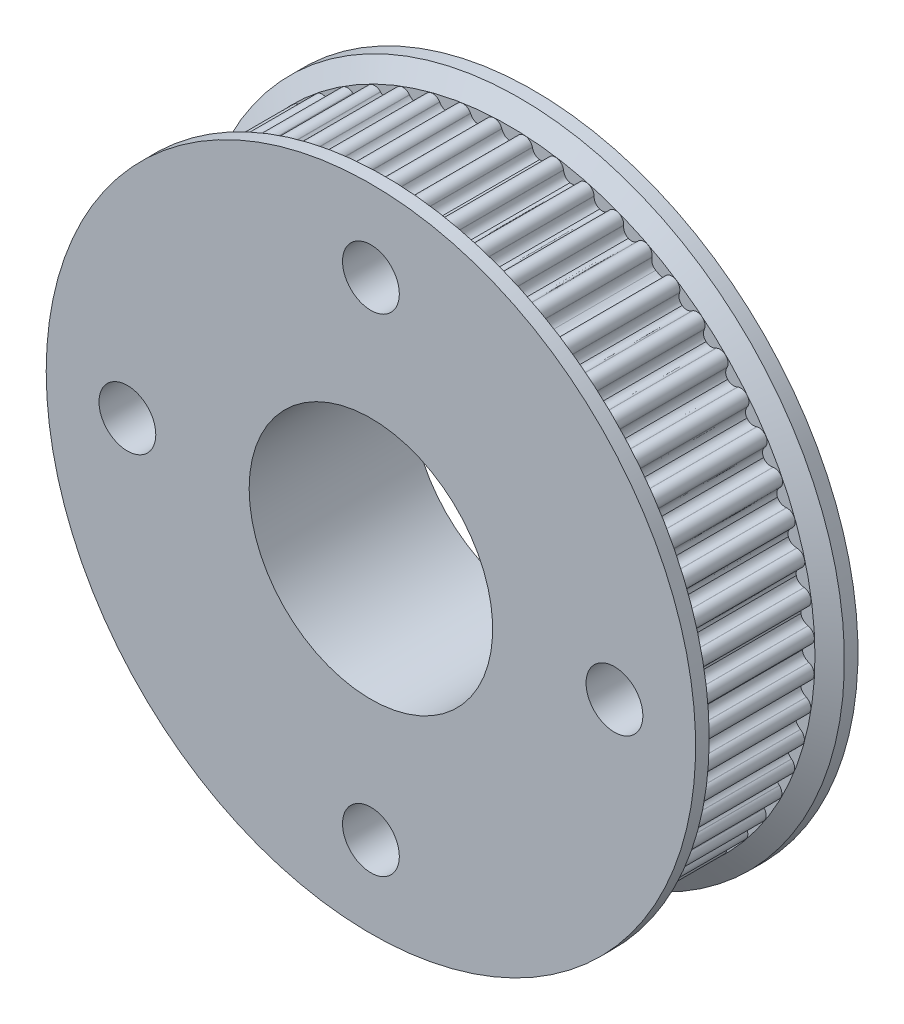
SolidWorks part; units mm, degrees
other "Camera1"
other "Camera2"
other "Camera3"
ref_plane "Front" through (0, 0, 0) normal (0, 0, 1) x (1, 0, 0)
ref_plane "Top" through (0, 0, 0) normal (0, 1, 0) x (1, 0, 0)
ref_plane "Right" through (0, 0, 0) normal (1, 0, 0) x (0, 0, -1)
sketch "Sketch1" plane through (0, 0, 0) normal (1, 0, 0) x (0, 0, -1)
  line L0 (0, 0) -> (-24.4032, 0) construction
  line L3 (0, 7.5) -> (0, 18.3141)
  line L4 (-1.5, 18.85) -> (-8.5, 18.85)
  line L5 (-10, 20) -> (-10, 7.5)
  line L6 (-10, 7.5) -> (0, 7.5)
  line L7 (0, 18.3141) -> (0, 20)
  line L9 (-0.836, 20) -> (-1.5, 18.85)
  line L10 (-10, 13.3586) -> (0, 13.3586) construction
  line L11 (-5, 18.85) -> (-5, 22.0506) construction
  line L12 (-9.164, 20) -> (-8.5, 18.85)
  line L15 (-10, 20) -> (-8.5, 18.85) construction
  line L16 (-1.5, 18.85) -> (0, 18.3141) construction
  line L17 (-10, 20) -> (-9.164, 20)
  line L18 (-0.836, 20) -> (0, 20)
  point P24 (-5, 13.3586)
  dimension "D2" = 10
  dimension "D3" = 7
  dimension "D4" = 37.7
  dimension "D5" = 40
  dimension "D6" = 120
  dimension "D8" = 15
revolve "Revolve1" add sketch "Sketch1" angle 360 about L0
ref_plane "Plane2" through (0, 0, 1.5) normal (0, 0, 1) x (1, 0, 0)
ref_plane "Plane3" through (0, 0, 8.5) normal (0, 0, 1) x (1, 0, 0)
sketch "Sketch3" plane through (0, 0, 1.5) normal (0, 0, 1) x (1, 0, 0)
  line L0 (0.4895, 18.4804) -> (0.4858, 18.4697)
  line L1 (-0.4323, 18.471) -> (-0.436, 18.4817)
  line L2 (-1.3914, 18.4344) -> (-1.394, 18.4234)
  line L3 (-2.3607, 18.3247) -> (-2.3654, 18.3349)
  line L4 (-3.3107, 18.188) -> (-3.3122, 18.1768)
  line L5 (-4.2632, 17.9775) -> (-4.269, 17.9872)
  line L6 (-5.1937, 17.7423) -> (-5.194, 17.731)
  line L7 (-6.119, 17.4334) -> (-6.1258, 17.4424)
  line L8 (-7.0199, 17.1022) -> (-7.019, 17.0909)
  line L9 (-7.9078, 16.6983) -> (-7.9155, 16.7066)
  line L10 (-8.7691, 16.2747) -> (-8.767, 16.2636)
  line L11 (-9.6099, 15.7803) -> (-9.6184, 15.7877)
  line L12 (-10.4222, 15.269) -> (-10.419, 15.2581)
  line L13 (-11.2067, 14.6893) -> (-11.216, 14.6958)
  line L14 (-11.9612, 14.0959) -> (-11.9568, 14.0855)
  line L15 (-12.6808, 13.4374) -> (-12.6907, 13.4429)
  line L16 (-13.3691, 12.7684) -> (-13.3637, 12.7585)
  line L17 (-14.0159, 12.0383) -> (-14.0263, 12.0427)
  line L18 (-14.6305, 11.301) -> (-14.6241, 11.2917)
  line L19 (-15.1975, 10.5073) -> (-15.2083, 10.5106)
  line L20 (-15.7316, 9.7098) -> (-15.7243, 9.7012)
  line L21 (-16.2125, 8.8612) -> (-16.2236, 8.8633)
  line L22 (-16.6604, 8.0122) -> (-16.6522, 8.0044)
  line L23 (-17.05, 7.118) -> (-17.0612, 7.1189)
  line L24 (-17.4066, 6.2268) -> (-17.3977, 6.22)
  line L25 (-17.7006, 5.2968) -> (-17.7119, 5.2965)
  line L26 (-17.9621, 4.3732) -> (-17.9525, 4.3673)
  line L27 (-18.1573, 3.4175) -> (-18.1685, 3.4161)
  line L28 (-18.3209, 2.4717) -> (-18.3107, 2.4669)
  line L29 (-18.415, 1.5008) -> (-18.426, 1.4983)
  line L30 (-18.4789, 0.5431) -> (-18.4682, 0.5394)
  line L31 (-18.471, -0.4323) -> (-18.4817, -0.436)
  line L32 (-18.4344, -1.3914) -> (-18.4234, -1.394)
  line L33 (-18.3247, -2.3607) -> (-18.3349, -2.3654)
  line L34 (-18.188, -3.3107) -> (-18.1768, -3.3122)
  line L35 (-17.9775, -4.2632) -> (-17.9872, -4.269)
  line L36 (-17.7423, -5.1937) -> (-17.731, -5.194)
  line L37 (-17.4334, -6.119) -> (-17.4424, -6.1258)
  line L38 (-17.1022, -7.0199) -> (-17.0909, -7.019)
  line L39 (-16.6983, -7.9078) -> (-16.7066, -7.9155)
  line L40 (-16.2747, -8.7691) -> (-16.2636, -8.767)
  line L41 (-15.7803, -9.6099) -> (-15.7877, -9.6184)
  line L42 (-15.269, -10.4222) -> (-15.2581, -10.419)
  line L43 (-14.6893, -11.2067) -> (-14.6958, -11.216)
  line L44 (-14.0959, -11.9612) -> (-14.0855, -11.9568)
  line L45 (-13.4374, -12.6808) -> (-13.4429, -12.6907)
  line L46 (-12.7684, -13.3691) -> (-12.7585, -13.3637)
  line L47 (-12.0383, -14.0159) -> (-12.0427, -14.0263)
  line L48 (-11.301, -14.6305) -> (-11.2917, -14.6241)
  line L49 (-10.5073, -15.1975) -> (-10.5106, -15.2083)
  line L50 (-9.7098, -15.7316) -> (-9.7012, -15.7243)
  line L51 (-8.8612, -16.2125) -> (-8.8633, -16.2236)
  line L52 (-8.0122, -16.6604) -> (-8.0044, -16.6522)
  line L53 (-7.118, -17.05) -> (-7.1189, -17.0612)
  line L54 (-6.2268, -17.4066) -> (-6.22, -17.3977)
  line L55 (-5.2968, -17.7006) -> (-5.2965, -17.7119)
  line L56 (-4.3732, -17.9621) -> (-4.3673, -17.9525)
  line L57 (-3.4175, -18.1573) -> (-3.4161, -18.1685)
  line L58 (-2.4717, -18.3209) -> (-2.4669, -18.3107)
  line L59 (-1.5008, -18.415) -> (-1.4983, -18.426)
  line L60 (-0.5431, -18.4789) -> (-0.5394, -18.4682)
  line L61 (0.4323, -18.471) -> (0.436, -18.4817)
  line L62 (1.3914, -18.4344) -> (1.394, -18.4234)
  line L63 (2.3607, -18.3247) -> (2.3654, -18.3349)
  line L64 (3.3107, -18.188) -> (3.3122, -18.1768)
  line L65 (4.2632, -17.9775) -> (4.269, -17.9872)
  line L66 (5.1937, -17.7423) -> (5.194, -17.731)
  line L67 (6.119, -17.4334) -> (6.1258, -17.4424)
  line L68 (7.0199, -17.1022) -> (7.019, -17.0909)
  line L69 (7.9078, -16.6983) -> (7.9155, -16.7066)
  line L70 (8.7691, -16.2747) -> (8.767, -16.2636)
  line L71 (9.6099, -15.7803) -> (9.6184, -15.7877)
  line L72 (10.4222, -15.269) -> (10.419, -15.2581)
  line L73 (11.2067, -14.6893) -> (11.216, -14.6958)
  line L74 (11.9612, -14.0959) -> (11.9568, -14.0855)
  line L75 (12.6808, -13.4374) -> (12.6907, -13.4429)
  line L76 (13.3691, -12.7684) -> (13.3637, -12.7585)
  line L77 (14.0159, -12.0383) -> (14.0263, -12.0427)
  line L78 (14.6305, -11.301) -> (14.6241, -11.2917)
  line L79 (15.1975, -10.5073) -> (15.2083, -10.5106)
  line L80 (15.7316, -9.7098) -> (15.7243, -9.7012)
  line L81 (16.2125, -8.8612) -> (16.2236, -8.8633)
  line L82 (16.6604, -8.0122) -> (16.6522, -8.0044)
  line L83 (17.05, -7.118) -> (17.0612, -7.1189)
  line L84 (17.4066, -6.2268) -> (17.3977, -6.22)
  line L85 (17.7006, -5.2968) -> (17.7119, -5.2965)
  line L86 (17.9621, -4.3732) -> (17.9525, -4.3673)
  line L87 (18.1573, -3.4175) -> (18.1685, -3.4161)
  line L88 (18.3209, -2.4717) -> (18.3107, -2.4669)
  line L89 (18.415, -1.5008) -> (18.426, -1.4983)
  line L90 (18.4789, -0.5431) -> (18.4682, -0.5394)
  line L91 (18.471, 0.4323) -> (18.4817, 0.436)
  line L92 (18.4344, 1.3914) -> (18.4234, 1.394)
  line L93 (18.3247, 2.3607) -> (18.3349, 2.3654)
  line L94 (18.188, 3.3107) -> (18.1768, 3.3122)
  line L95 (17.9775, 4.2632) -> (17.9872, 4.269)
  line L96 (17.7423, 5.1937) -> (17.731, 5.194)
  line L97 (17.4334, 6.119) -> (17.4424, 6.1258)
  line L98 (17.1022, 7.0199) -> (17.0909, 7.019)
  line L99 (16.6983, 7.9078) -> (16.7066, 7.9155)
  line L100 (16.2747, 8.7691) -> (16.2636, 8.767)
  line L101 (15.7803, 9.6099) -> (15.7877, 9.6184)
  line L102 (15.269, 10.4222) -> (15.2581, 10.419)
  line L103 (14.6893, 11.2067) -> (14.6958, 11.216)
  line L104 (14.0959, 11.9612) -> (14.0855, 11.9568)
  line L105 (13.4374, 12.6808) -> (13.4429, 12.6907)
  line L106 (12.7684, 13.3691) -> (12.7585, 13.3637)
  line L107 (12.0383, 14.0159) -> (12.0427, 14.0263)
  line L108 (11.301, 14.6305) -> (11.2917, 14.6241)
  line L109 (10.5073, 15.1975) -> (10.5106, 15.2083)
  line L110 (9.7098, 15.7316) -> (9.7012, 15.7243)
  line L111 (8.8141, 16.2382) -> (8.8162, 16.2492)
  line L112 (7.9639, 16.6835) -> (7.9561, 16.6753)
  line L113 (7.0685, 17.0705) -> (7.0694, 17.0818)
  line L114 (6.1763, 17.4246) -> (6.1695, 17.4156)
  line L115 (5.2454, 17.7159) -> (5.2452, 17.7272)
  line L116 (4.3211, 17.9748) -> (4.3153, 17.9651)
  line L117 (3.3649, 18.1671) -> (3.3634, 18.1783)
  line L118 (2.4186, 18.328) -> (2.4138, 18.3178)
  line L119 (1.4475, 18.4193) -> (1.4449, 18.4303)
  arc A0 (-0.436, 18.4817) -> (-1.3914, 18.4344) centre (-0.9065, 18.3126) ccw
  arc A1 (-2.3654, 18.3349) -> (-3.3107, 18.188) centre (-2.8157, 18.1175) ccw
  arc A2 (-4.269, 17.9872) -> (-5.1937, 17.7423) centre (-4.6941, 17.7239) ccw
  arc A3 (-6.1258, 17.4424) -> (-7.0199, 17.1022) centre (-6.521, 17.1362) ccw
  arc A4 (-7.9155, 16.7066) -> (-8.7691, 16.2747) centre (-8.2765, 16.3607) ccw
  arc A5 (-9.6184, 15.7877) -> (-10.4222, 15.269) centre (-9.9413, 15.4059) ccw
  arc A6 (-11.216, 14.6958) -> (-11.9612, 14.0959) centre (-11.4972, 14.2824) ccw
  arc A7 (-12.6907, 13.4429) -> (-13.3691, 12.7684) centre (-12.9272, 13.0023) ccw
  arc A8 (-14.0263, 12.0427) -> (-14.6305, 11.301) centre (-14.2155, 11.5798) ccw
  arc A9 (-15.2083, 10.5106) -> (-15.7316, 9.7098) centre (-15.348, 10.0305) ccw
  arc A10 (-16.2236, 8.8633) -> (-16.6604, 8.0122) centre (-16.3124, 8.3712) ccw
  arc A11 (-17.0612, 7.1189) -> (-17.4066, 6.2268) centre (-17.0981, 6.6203) ccw
  arc A12 (-17.7119, 5.2965) -> (-17.9621, 4.3732) centre (-17.6964, 4.7968) ccw
  arc A13 (-18.1685, 3.4161) -> (-18.3209, 2.4717) centre (-18.1009, 2.9207) ccw
  arc A14 (-18.426, 1.4983) -> (-18.4789, 0.5431) centre (-18.307, 1.0127) ccw
  arc A15 (-18.4817, -0.436) -> (-18.4344, -1.3914) centre (-18.3126, -0.9065) ccw
  arc A16 (-18.3349, -2.3654) -> (-18.188, -3.3107) centre (-18.1175, -2.8157) ccw
  arc A17 (-17.9872, -4.269) -> (-17.7423, -5.1937) centre (-17.7239, -4.6941) ccw
  arc A18 (-17.4424, -6.1258) -> (-17.1022, -7.0199) centre (-17.1362, -6.521) ccw
  arc A19 (-16.7066, -7.9155) -> (-16.2747, -8.7691) centre (-16.3607, -8.2765) ccw
  arc A20 (-15.7877, -9.6184) -> (-15.269, -10.4222) centre (-15.4059, -9.9413) ccw
  arc A21 (-14.6958, -11.216) -> (-14.0959, -11.9612) centre (-14.2824, -11.4972) ccw
  arc A22 (-13.4429, -12.6907) -> (-12.7684, -13.3691) centre (-13.0023, -12.9272) ccw
  arc A23 (-12.0427, -14.0263) -> (-11.301, -14.6305) centre (-11.5798, -14.2155) ccw
  arc A24 (-10.5106, -15.2083) -> (-9.7098, -15.7316) centre (-10.0305, -15.348) ccw
  arc A25 (-8.8633, -16.2236) -> (-8.0122, -16.6604) centre (-8.3712, -16.3124) ccw
  arc A26 (-7.1189, -17.0612) -> (-6.2268, -17.4066) centre (-6.6203, -17.0981) ccw
  arc A27 (-5.2965, -17.7119) -> (-4.3732, -17.9621) centre (-4.7968, -17.6964) ccw
  arc A28 (-3.4161, -18.1685) -> (-2.4717, -18.3209) centre (-2.9207, -18.1009) ccw
  arc A29 (-1.4983, -18.426) -> (-0.5431, -18.4789) centre (-1.0127, -18.307) ccw
  arc A30 (0.436, -18.4817) -> (1.3914, -18.4344) centre (0.9065, -18.3126) ccw
  arc A31 (2.3654, -18.3349) -> (3.3107, -18.188) centre (2.8157, -18.1175) ccw
  arc A32 (4.269, -17.9872) -> (5.1937, -17.7423) centre (4.6941, -17.7239) ccw
  arc A33 (6.1258, -17.4424) -> (7.0199, -17.1022) centre (6.521, -17.1362) ccw
  arc A34 (7.9155, -16.7066) -> (8.7691, -16.2747) centre (8.2765, -16.3607) ccw
  arc A35 (9.6184, -15.7877) -> (10.4222, -15.269) centre (9.9413, -15.4059) ccw
  arc A36 (11.216, -14.6958) -> (11.9612, -14.0959) centre (11.4972, -14.2824) ccw
  arc A37 (12.6907, -13.4429) -> (13.3691, -12.7684) centre (12.9272, -13.0023) ccw
  arc A38 (14.0263, -12.0427) -> (14.6305, -11.301) centre (14.2155, -11.5798) ccw
  arc A39 (15.2083, -10.5106) -> (15.7316, -9.7098) centre (15.348, -10.0305) ccw
  arc A40 (16.2236, -8.8633) -> (16.6604, -8.0122) centre (16.3124, -8.3712) ccw
  arc A41 (17.0612, -7.1189) -> (17.4066, -6.2268) centre (17.0981, -6.6203) ccw
  arc A42 (17.7119, -5.2965) -> (17.9621, -4.3732) centre (17.6964, -4.7968) ccw
  arc A43 (18.1685, -3.4161) -> (18.3209, -2.4717) centre (18.1009, -2.9207) ccw
  arc A44 (18.426, -1.4983) -> (18.4789, -0.5431) centre (18.307, -1.0127) ccw
  arc A45 (18.4817, 0.436) -> (18.4344, 1.3914) centre (18.3126, 0.9065) ccw
  arc A46 (18.3349, 2.3654) -> (18.188, 3.3107) centre (18.1175, 2.8157) ccw
  arc A47 (17.9872, 4.269) -> (17.7423, 5.1937) centre (17.7239, 4.6941) ccw
  arc A48 (17.4424, 6.1258) -> (17.1022, 7.0199) centre (17.1362, 6.521) ccw
  arc A49 (16.7066, 7.9155) -> (16.2747, 8.7691) centre (16.3607, 8.2765) ccw
  arc A50 (15.7877, 9.6184) -> (15.269, 10.4222) centre (15.4059, 9.9413) ccw
  arc A51 (14.6958, 11.216) -> (14.0959, 11.9612) centre (14.2824, 11.4972) ccw
  arc A52 (13.4429, 12.6907) -> (12.7684, 13.3691) centre (13.0023, 12.9272) ccw
  arc A53 (12.0427, 14.0263) -> (11.301, 14.6305) centre (11.5798, 14.2155) ccw
  arc A54 (10.5106, 15.2083) -> (9.7098, 15.7316) centre (10.0305, 15.348) ccw
  arc A55 (8.8162, 16.2492) -> (7.9639, 16.6835) centre (8.3239, 16.3366) ccw
  arc A56 (7.0694, 17.0818) -> (6.1763, 17.4246) centre (6.5707, 17.1172) ccw
  arc A57 (5.2452, 17.7272) -> (4.3211, 17.9748) centre (4.7454, 17.7103) ccw
  arc A58 (3.3634, 18.1783) -> (2.4186, 18.328) centre (2.8682, 18.1093) ccw
  arc A59 (1.4449, 18.4303) -> (0.4895, 18.4804) centre (0.9596, 18.3099) ccw
  spline S0 degree 3 poles (0.4858, 18.4697) (0.4077, 18.2495) (0.2403, 18.0862) (0.0262, 18.0851) knots 0 0 0 0 1 1 1 1
  spline S1 degree 3 poles (0.0262, 18.0851) (-0.1878, 18.0868) (-0.3548, 18.2506) (-0.4323, 18.471) knots 0 0 0 0 1 1 1 1
  spline S2 degree 3 poles (-1.394, 18.4234) (-1.4515, 18.1875) (-1.5982, 18.0156) (-1.8382, 17.9913) knots 0 0 0 0 1 1 1 1
  spline S3 degree 3 poles (-1.8382, 17.9913) (-2.0782, 17.9665) (-2.2567, 18.1053) (-2.3607, 18.3247) knots 0 0 0 0 1 1 1 1
  spline S4 degree 3 poles (-3.3122, 18.1768) (-3.3447, 17.9362) (-3.4726, 17.7498) (-3.7088, 17.7006) knots 0 0 0 0 1 1 1 1
  spline S5 degree 3 poles (-3.7088, 17.7006) (-3.9448, 17.6509) (-4.1368, 17.7702) (-4.2632, 17.9775) knots 0 0 0 0 1 1 1 1
  spline S6 degree 3 poles (-5.194, 17.731) (-5.2012, 17.4883) (-5.309, 17.2896) (-5.5387, 17.216) knots 0 0 0 0 1 1 1 1
  spline S7 degree 3 poles (-5.5387, 17.216) (-5.7682, 17.1418) (-5.9717, 17.2404) (-6.119, 17.4334) knots 0 0 0 0 1 1 1 1
  spline S8 degree 3 poles (-7.019, 17.0909) (-7.0007, 16.8488) (-7.0871, 16.6399) (-7.3079, 16.5427) knots 0 0 0 0 1 1 1 1
  spline S9 degree 3 poles (-7.3079, 16.5427) (-7.5284, 16.445) (-7.7411, 16.5218) (-7.9078, 16.6983) knots 0 0 0 0 1 1 1 1
  spline S10 degree 3 poles (-8.767, 16.2636) (-8.7236, 16.0248) (-8.7877, 15.808) (-8.9971, 15.6882) knots 0 0 0 0 1 1 1 1
  spline S11 degree 3 poles (-8.9971, 15.6882) (-9.2062, 15.568) (-9.4256, 15.6221) (-9.6099, 15.7803) knots 0 0 0 0 1 1 1 1
  spline S12 degree 3 poles (-10.419, 15.2581) (-10.3508, 15.0251) (-10.3919, 14.8028) (-10.5876, 14.6618) knots 0 0 0 0 1 1 1 1
  spline S13 degree 3 poles (-10.5876, 14.6618) (-10.783, 14.5204) (-11.007, 14.5513) (-11.2067, 14.6893) knots 0 0 0 0 1 1 1 1
  spline S14 degree 3 poles (-11.9568, 14.0855) (-11.8647, 13.8608) (-11.8823, 13.6355) (-12.0622, 13.4748) knots 0 0 0 0 1 1 1 1
  spline S15 degree 3 poles (-12.0622, 13.4748) (-12.2418, 13.3137) (-12.4677, 13.321) (-12.6808, 13.4374) knots 0 0 0 0 1 1 1 1
  spline S16 degree 3 poles (-13.3637, 12.7585) (-13.2485, 12.5447) (-13.2425, 12.3187) (-13.4046, 12.1401) knots 0 0 0 0 1 1 1 1
  spline S17 degree 3 poles (-13.4046, 12.1401) (-13.5664, 11.9611) (-13.7918, 11.9448) (-14.0159, 12.0383) knots 0 0 0 0 1 1 1 1
  spline S18 degree 3 poles (-14.6241, 11.2917) (-14.4872, 11.0912) (-14.4576, 10.867) (-14.6002, 10.6725) knots 0 0 0 0 1 1 1 1
  spline S19 degree 3 poles (-14.6002, 10.6725) (-14.7423, 10.4776) (-14.9648, 10.4378) (-15.1975, 10.5073) knots 0 0 0 0 1 1 1 1
  spline S20 degree 3 poles (-15.7243, 9.7012) (-15.5672, 9.5161) (-15.5143, 9.2963) (-15.6358, 9.0879) knots 0 0 0 0 1 1 1 1
  spline S21 degree 3 poles (-15.6358, 9.0879) (-15.7568, 8.8792) (-15.9739, 8.8163) (-16.2125, 8.8612) knots 0 0 0 0 1 1 1 1
  spline S22 degree 3 poles (-16.6522, 8.0044) (-16.4766, 7.8367) (-16.4011, 7.6237) (-16.5001, 7.4037) knots 0 0 0 0 1 1 1 1
  spline S23 degree 3 poles (-16.5001, 7.4037) (-16.5986, 7.1835) (-16.808, 7.0983) (-17.05, 7.118) knots 0 0 0 0 1 1 1 1
  spline S24 degree 3 poles (-17.3977, 6.22) (-17.2055, 6.0715) (-17.1081, 5.8675) (-17.1836, 5.6384) knots 0 0 0 0 1 1 1 1
  spline S25 degree 3 poles (-17.1836, 5.6384) (-17.2585, 5.4091) (-17.4579, 5.3025) (-17.7006, 5.2968) knots 0 0 0 0 1 1 1 1
  spline S26 degree 3 poles (-17.9525, 4.3673) (-17.7459, 4.2398) (-17.6277, 4.0471) (-17.6788, 3.8114) knots 0 0 0 0 1 1 1 1
  spline S27 degree 3 poles (-17.6788, 3.8114) (-17.7294, 3.5755) (-17.9165, 3.4486) (-18.1573, 3.4175) knots 0 0 0 0 1 1 1 1
  spline S28 degree 3 poles (-18.3107, 2.4669) (-18.0919, 2.3616) (-17.9542, 2.1823) (-17.9804, 1.9425) knots 0 0 0 0 1 1 1 1
  spline S29 degree 3 poles (-17.9804, 1.9425) (-18.006, 1.7027) (-18.1788, 1.5569) (-18.415, 1.5008) knots 0 0 0 0 1 1 1 1
  spline S30 degree 3 poles (-18.4682, 0.5394) (-18.2396, 0.4576) (-18.0839, 0.2937) (-18.0849, 0.0524) knots 0 0 0 0 1 1 1 1
  spline S31 degree 3 poles (-18.0849, 0.0524) (-18.0853, -0.1888) (-18.242, -0.3518) (-18.471, -0.4323) knots 0 0 0 0 1 1 1 1
  spline S32 degree 3 poles (-18.4234, -1.394) (-18.1875, -1.4515) (-18.0156, -1.5982) (-17.9913, -1.8382) knots 0 0 0 0 1 1 1 1
  spline S33 degree 3 poles (-17.9913, -1.8382) (-17.9665, -2.0782) (-18.1053, -2.2567) (-18.3247, -2.3607) knots 0 0 0 0 1 1 1 1
  spline S34 degree 3 poles (-18.1768, -3.3122) (-17.9362, -3.3447) (-17.7498, -3.4726) (-17.7006, -3.7088) knots 0 0 0 0 1 1 1 1
  spline S35 degree 3 poles (-17.7006, -3.7088) (-17.6509, -3.9448) (-17.7702, -4.1368) (-17.9775, -4.2632) knots 0 0 0 0 1 1 1 1
  spline S36 degree 3 poles (-17.731, -5.194) (-17.4883, -5.2012) (-17.2896, -5.309) (-17.216, -5.5387) knots 0 0 0 0 1 1 1 1
  spline S37 degree 3 poles (-17.216, -5.5387) (-17.1418, -5.7682) (-17.2404, -5.9717) (-17.4334, -6.119) knots 0 0 0 0 1 1 1 1
  spline S38 degree 3 poles (-17.0909, -7.019) (-16.8488, -7.0007) (-16.6399, -7.0871) (-16.5427, -7.3079) knots 0 0 0 0 1 1 1 1
  spline S39 degree 3 poles (-16.5427, -7.3079) (-16.445, -7.5284) (-16.5218, -7.7411) (-16.6983, -7.9078) knots 0 0 0 0 1 1 1 1
  spline S40 degree 3 poles (-16.2636, -8.767) (-16.0248, -8.7236) (-15.808, -8.7877) (-15.6882, -8.9971) knots 0 0 0 0 1 1 1 1
  spline S41 degree 3 poles (-15.6882, -8.9971) (-15.568, -9.2062) (-15.6221, -9.4256) (-15.7803, -9.6099) knots 0 0 0 0 1 1 1 1
  spline S42 degree 3 poles (-15.2581, -10.419) (-15.0251, -10.3508) (-14.8028, -10.3919) (-14.6618, -10.5876) knots 0 0 0 0 1 1 1 1
  spline S43 degree 3 poles (-14.6618, -10.5876) (-14.5204, -10.783) (-14.5513, -11.007) (-14.6893, -11.2067) knots 0 0 0 0 1 1 1 1
  spline S44 degree 3 poles (-14.0855, -11.9568) (-13.8608, -11.8647) (-13.6355, -11.8823) (-13.4748, -12.0622) knots 0 0 0 0 1 1 1 1
  spline S45 degree 3 poles (-13.4748, -12.0622) (-13.3137, -12.2418) (-13.321, -12.4677) (-13.4374, -12.6808) knots 0 0 0 0 1 1 1 1
  spline S46 degree 3 poles (-12.7585, -13.3637) (-12.5447, -13.2485) (-12.3187, -13.2425) (-12.1401, -13.4046) knots 0 0 0 0 1 1 1 1
  spline S47 degree 3 poles (-12.1401, -13.4046) (-11.9611, -13.5664) (-11.9448, -13.7918) (-12.0383, -14.0159) knots 0 0 0 0 1 1 1 1
  spline S48 degree 3 poles (-11.2917, -14.6241) (-11.0912, -14.4872) (-10.867, -14.4576) (-10.6725, -14.6002) knots 0 0 0 0 1 1 1 1
  spline S49 degree 3 poles (-10.6725, -14.6002) (-10.4776, -14.7423) (-10.4378, -14.9648) (-10.5073, -15.1975) knots 0 0 0 0 1 1 1 1
  spline S50 degree 3 poles (-9.7012, -15.7243) (-9.5161, -15.5672) (-9.2963, -15.5143) (-9.0879, -15.6358) knots 0 0 0 0 1 1 1 1
  spline S51 degree 3 poles (-9.0879, -15.6358) (-8.8792, -15.7568) (-8.8163, -15.9739) (-8.8612, -16.2125) knots 0 0 0 0 1 1 1 1
  spline S52 degree 3 poles (-8.0044, -16.6522) (-7.8367, -16.4766) (-7.6237, -16.4011) (-7.4037, -16.5001) knots 0 0 0 0 1 1 1 1
  spline S53 degree 3 poles (-7.4037, -16.5001) (-7.1835, -16.5986) (-7.0983, -16.808) (-7.118, -17.05) knots 0 0 0 0 1 1 1 1
  spline S54 degree 3 poles (-6.22, -17.3977) (-6.0715, -17.2055) (-5.8675, -17.1081) (-5.6384, -17.1836) knots 0 0 0 0 1 1 1 1
  spline S55 degree 3 poles (-5.6384, -17.1836) (-5.4091, -17.2585) (-5.3025, -17.4579) (-5.2968, -17.7006) knots 0 0 0 0 1 1 1 1
  spline S56 degree 3 poles (-4.3673, -17.9525) (-4.2398, -17.7459) (-4.0471, -17.6277) (-3.8114, -17.6788) knots 0 0 0 0 1 1 1 1
  spline S57 degree 3 poles (-3.8114, -17.6788) (-3.5755, -17.7294) (-3.4486, -17.9165) (-3.4175, -18.1573) knots 0 0 0 0 1 1 1 1
  spline S58 degree 3 poles (-2.4669, -18.3107) (-2.3616, -18.0919) (-2.1823, -17.9542) (-1.9425, -17.9804) knots 0 0 0 0 1 1 1 1
  spline S59 degree 3 poles (-1.9425, -17.9804) (-1.7027, -18.006) (-1.5569, -18.1788) (-1.5008, -18.415) knots 0 0 0 0 1 1 1 1
  spline S60 degree 3 poles (-0.5394, -18.4682) (-0.4576, -18.2396) (-0.2937, -18.0839) (-0.0524, -18.0849) knots 0 0 0 0 1 1 1 1
  spline S61 degree 3 poles (-0.0524, -18.0849) (0.1888, -18.0853) (0.3518, -18.242) (0.4323, -18.471) knots 0 0 0 0 1 1 1 1
  spline S62 degree 3 poles (1.394, -18.4234) (1.4515, -18.1875) (1.5982, -18.0156) (1.8382, -17.9913) knots 0 0 0 0 1 1 1 1
  spline S63 degree 3 poles (1.8382, -17.9913) (2.0782, -17.9665) (2.2567, -18.1053) (2.3607, -18.3247) knots 0 0 0 0 1 1 1 1
  spline S64 degree 3 poles (3.3122, -18.1768) (3.3447, -17.9362) (3.4726, -17.7498) (3.7088, -17.7006) knots 0 0 0 0 1 1 1 1
  spline S65 degree 3 poles (3.7088, -17.7006) (3.9448, -17.6509) (4.1368, -17.7702) (4.2632, -17.9775) knots 0 0 0 0 1 1 1 1
  spline S66 degree 3 poles (5.194, -17.731) (5.2012, -17.4883) (5.309, -17.2896) (5.5387, -17.216) knots 0 0 0 0 1 1 1 1
  spline S67 degree 3 poles (5.5387, -17.216) (5.7682, -17.1418) (5.9717, -17.2404) (6.119, -17.4334) knots 0 0 0 0 1 1 1 1
  spline S68 degree 3 poles (7.019, -17.0909) (7.0007, -16.8488) (7.0871, -16.6399) (7.3079, -16.5427) knots 0 0 0 0 1 1 1 1
  spline S69 degree 3 poles (7.3079, -16.5427) (7.5284, -16.445) (7.7411, -16.5218) (7.9078, -16.6983) knots 0 0 0 0 1 1 1 1
  spline S70 degree 3 poles (8.767, -16.2636) (8.7236, -16.0248) (8.7877, -15.808) (8.9971, -15.6882) knots 0 0 0 0 1 1 1 1
  spline S71 degree 3 poles (8.9971, -15.6882) (9.2062, -15.568) (9.4256, -15.6221) (9.6099, -15.7803) knots 0 0 0 0 1 1 1 1
  spline S72 degree 3 poles (10.419, -15.2581) (10.3508, -15.0251) (10.3919, -14.8028) (10.5876, -14.6618) knots 0 0 0 0 1 1 1 1
  spline S73 degree 3 poles (10.5876, -14.6618) (10.783, -14.5204) (11.007, -14.5513) (11.2067, -14.6893) knots 0 0 0 0 1 1 1 1
  spline S74 degree 3 poles (11.9568, -14.0855) (11.8647, -13.8608) (11.8823, -13.6355) (12.0622, -13.4748) knots 0 0 0 0 1 1 1 1
  spline S75 degree 3 poles (12.0622, -13.4748) (12.2418, -13.3137) (12.4677, -13.321) (12.6808, -13.4374) knots 0 0 0 0 1 1 1 1
  spline S76 degree 3 poles (13.3637, -12.7585) (13.2485, -12.5447) (13.2425, -12.3187) (13.4046, -12.1401) knots 0 0 0 0 1 1 1 1
  spline S77 degree 3 poles (13.4046, -12.1401) (13.5664, -11.9611) (13.7918, -11.9448) (14.0159, -12.0383) knots 0 0 0 0 1 1 1 1
  spline S78 degree 3 poles (14.6241, -11.2917) (14.4872, -11.0912) (14.4576, -10.867) (14.6002, -10.6725) knots 0 0 0 0 1 1 1 1
  spline S79 degree 3 poles (14.6002, -10.6725) (14.7423, -10.4776) (14.9648, -10.4378) (15.1975, -10.5073) knots 0 0 0 0 1 1 1 1
  spline S80 degree 3 poles (15.7243, -9.7012) (15.5672, -9.5161) (15.5143, -9.2963) (15.6358, -9.0879) knots 0 0 0 0 1 1 1 1
  spline S81 degree 3 poles (15.6358, -9.0879) (15.7568, -8.8792) (15.9739, -8.8163) (16.2125, -8.8612) knots 0 0 0 0 1 1 1 1
  spline S82 degree 3 poles (16.6522, -8.0044) (16.4766, -7.8367) (16.4011, -7.6237) (16.5001, -7.4037) knots 0 0 0 0 1 1 1 1
  spline S83 degree 3 poles (16.5001, -7.4037) (16.5986, -7.1835) (16.808, -7.0983) (17.05, -7.118) knots 0 0 0 0 1 1 1 1
  spline S84 degree 3 poles (17.3977, -6.22) (17.2055, -6.0715) (17.1081, -5.8675) (17.1836, -5.6384) knots 0 0 0 0 1 1 1 1
  spline S85 degree 3 poles (17.1836, -5.6384) (17.2585, -5.4091) (17.4579, -5.3025) (17.7006, -5.2968) knots 0 0 0 0 1 1 1 1
  spline S86 degree 3 poles (17.9525, -4.3673) (17.7459, -4.2398) (17.6277, -4.0471) (17.6788, -3.8114) knots 0 0 0 0 1 1 1 1
  spline S87 degree 3 poles (17.6788, -3.8114) (17.7294, -3.5755) (17.9165, -3.4486) (18.1573, -3.4175) knots 0 0 0 0 1 1 1 1
  spline S88 degree 3 poles (18.3107, -2.4669) (18.0919, -2.3616) (17.9542, -2.1823) (17.9804, -1.9425) knots 0 0 0 0 1 1 1 1
  spline S89 degree 3 poles (17.9804, -1.9425) (18.006, -1.7027) (18.1788, -1.5569) (18.415, -1.5008) knots 0 0 0 0 1 1 1 1
  spline S90 degree 3 poles (18.4682, -0.5394) (18.2396, -0.4576) (18.0839, -0.2937) (18.0849, -0.0524) knots 0 0 0 0 1 1 1 1
  spline S91 degree 3 poles (18.0849, -0.0524) (18.0853, 0.1888) (18.242, 0.3518) (18.471, 0.4323) knots 0 0 0 0 1 1 1 1
  spline S92 degree 3 poles (18.4234, 1.394) (18.1875, 1.4515) (18.0156, 1.5982) (17.9913, 1.8382) knots 0 0 0 0 1 1 1 1
  spline S93 degree 3 poles (17.9913, 1.8382) (17.9665, 2.0782) (18.1053, 2.2567) (18.3247, 2.3607) knots 0 0 0 0 1 1 1 1
  spline S94 degree 3 poles (18.1768, 3.3122) (17.9362, 3.3447) (17.7498, 3.4726) (17.7006, 3.7088) knots 0 0 0 0 1 1 1 1
  spline S95 degree 3 poles (17.7006, 3.7088) (17.6509, 3.9448) (17.7702, 4.1368) (17.9775, 4.2632) knots 0 0 0 0 1 1 1 1
  spline S96 degree 3 poles (17.731, 5.194) (17.4883, 5.2012) (17.2896, 5.309) (17.216, 5.5387) knots 0 0 0 0 1 1 1 1
  spline S97 degree 3 poles (17.216, 5.5387) (17.1418, 5.7682) (17.2404, 5.9717) (17.4334, 6.119) knots 0 0 0 0 1 1 1 1
  spline S98 degree 3 poles (17.0909, 7.019) (16.8488, 7.0007) (16.6399, 7.0871) (16.5427, 7.3079) knots 0 0 0 0 1 1 1 1
  spline S99 degree 3 poles (16.5427, 7.3079) (16.445, 7.5284) (16.5218, 7.7411) (16.6983, 7.9078) knots 0 0 0 0 1 1 1 1
  spline S100 degree 3 poles (16.2636, 8.767) (16.0248, 8.7236) (15.808, 8.7877) (15.6882, 8.9971) knots 0 0 0 0 1 1 1 1
  spline S101 degree 3 poles (15.6882, 8.9971) (15.568, 9.2062) (15.6221, 9.4256) (15.7803, 9.6099) knots 0 0 0 0 1 1 1 1
  spline S102 degree 3 poles (15.2581, 10.419) (15.0251, 10.3508) (14.8028, 10.3919) (14.6618, 10.5876) knots 0 0 0 0 1 1 1 1
  spline S103 degree 3 poles (14.6618, 10.5876) (14.5204, 10.783) (14.5513, 11.007) (14.6893, 11.2067) knots 0 0 0 0 1 1 1 1
  spline S104 degree 3 poles (14.0855, 11.9568) (13.8608, 11.8647) (13.6355, 11.8823) (13.4748, 12.0622) knots 0 0 0 0 1 1 1 1
  spline S105 degree 3 poles (13.4748, 12.0622) (13.3137, 12.2418) (13.321, 12.4677) (13.4374, 12.6808) knots 0 0 0 0 1 1 1 1
  spline S106 degree 3 poles (12.7585, 13.3637) (12.5447, 13.2485) (12.3187, 13.2425) (12.1401, 13.4046) knots 0 0 0 0 1 1 1 1
  spline S107 degree 3 poles (12.1401, 13.4046) (11.9611, 13.5664) (11.9448, 13.7918) (12.0383, 14.0159) knots 0 0 0 0 1 1 1 1
  spline S108 degree 3 poles (11.2917, 14.6241) (11.0912, 14.4872) (10.867, 14.4576) (10.6725, 14.6002) knots 0 0 0 0 1 1 1 1
  spline S109 degree 3 poles (10.6725, 14.6002) (10.4776, 14.7423) (10.4378, 14.9648) (10.5073, 15.1975) knots 0 0 0 0 1 1 1 1
  spline S110 degree 3 poles (9.7012, 15.7243) (9.5161, 15.5672) (9.5993, 15.3388) (9.0425, 15.6621) knots 0 0 0 0 1 1 1 1
  spline S111 degree 3 poles (9.0425, 15.6621) (8.8334, 15.7824) (8.77, 15.9994) (8.8141, 16.2382) knots 0 0 0 0 1 1 1 1
  spline S112 degree 3 poles (7.9561, 16.6753) (7.7889, 16.4993) (7.5761, 16.4231) (7.3558, 16.5215) knots 0 0 0 0 1 1 1 1
  spline S113 degree 3 poles (7.3558, 16.5215) (7.1353, 16.6193) (7.0495, 16.8285) (7.0685, 17.0705) knots 0 0 0 0 1 1 1 1
  spline S114 degree 3 poles (6.1695, 17.4156) (6.0216, 17.2231) (5.8179, 17.125) (5.5886, 17.1999) knots 0 0 0 0 1 1 1 1
  spline S115 degree 3 poles (5.5886, 17.1999) (5.3591, 17.2741) (5.2519, 17.4732) (5.2454, 17.7159) knots 0 0 0 0 1 1 1 1
  spline S116 degree 3 poles (4.3153, 17.9651) (4.1883, 17.7581) (3.996, 17.6394) (3.7601, 17.6898) knots 0 0 0 0 1 1 1 1
  spline S117 degree 3 poles (3.7601, 17.6898) (3.5241, 17.7397) (3.3967, 17.9264) (3.3649, 18.1671) knots 0 0 0 0 1 1 1 1
  spline S118 degree 3 poles (2.4138, 18.3178) (2.3091, 18.0986) (2.1303, 17.9604) (1.8904, 17.9859) knots 0 0 0 0 1 1 1 1
  spline S119 degree 3 poles (1.8904, 17.9859) (1.6505, 18.0109) (1.5042, 18.1832) (1.4475, 18.4193) knots 0 0 0 0 1 1 1 1
extrude "Cut-Extrude1" cut sketch "Sketch3" along normal up to surface (7 mm away) flip side to cut up to plane "Plane3"
sketch "Sketch4" plane through (0, 0, 10) normal (0, 0, 1) x (1, 0, 0)
  circle A0 centre (0, 15) radius 1.75
  circle A1 centre (15, 0) radius 1.75
  circle A2 centre (0, -15) radius 1.75
  circle A3 centre (-15, 0) radius 1.75
  point P12 (0, 0)
  dimension "D1" = 3.5
  dimension "D2" = 15
  dimension "D3" = 4
extrude "Cut-Extrude2" cut sketch "Sketch4" against normal up to surface (10 mm away) up to face at (-20, 0, 0)
sketch "Sketch5" plane through (0, 0, 0) normal (0, 0, -1) x (-1, 0, 0)
  circle A0 centre (0, 15) radius 3
  circle A1 centre (15, 0) radius 3
  circle A2 centre (0, -15) radius 3
  circle A3 centre (-15, 0) radius 3
  point P12 (0, 0)
  dimension "D1" = 6
  dimension "D2" = 4
extrude "Cut-Extrude3" cut sketch "Sketch5" against normal blind 3
